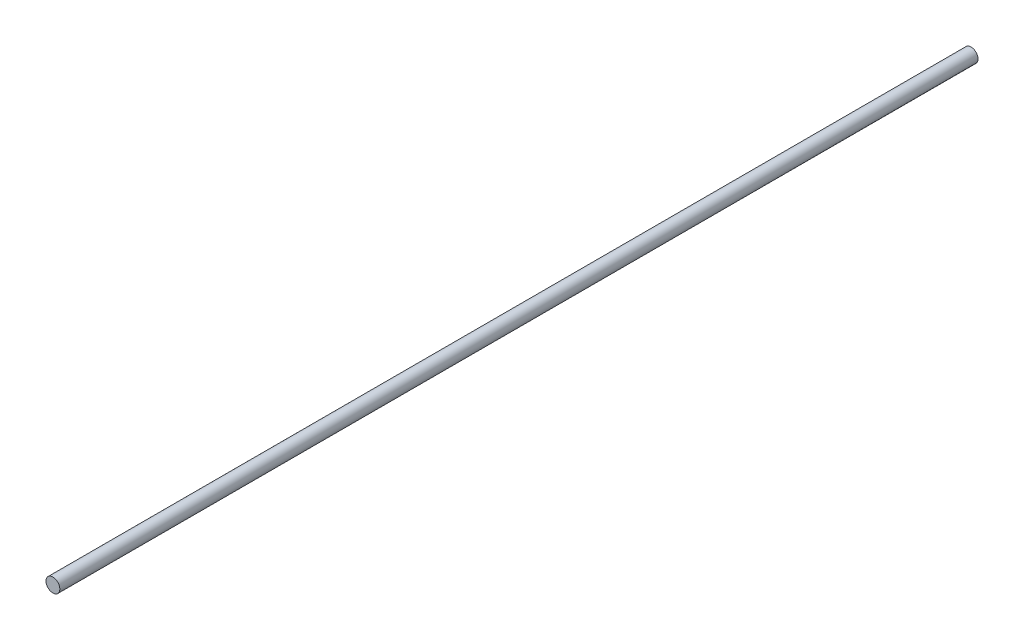
SolidWorks part; units mm, degrees
ref_plane "Front Plane" through (0, 0, 0) normal (0, 0, 1) x (1, 0, 0)
ref_plane "Top Plane" through (0, 0, 0) normal (0, 1, 0) x (1, 0, 0)
ref_plane "Right Plane" through (0, 0, 0) normal (1, 0, 0) x (0, 0, -1)
sketch "Sketch1" plane through (0, 0, 0) normal (0, 0, 1) x (1, 0, 0)
  circle A0 centre (0, 0) radius 4.7625
  dimension "D1" = 9.525
extrude "Boss-Extrude1" add sketch "Sketch1" along normal blind 631.19
equation "\"deflection\"= 0.009in'maximum deflection"
equation "\"diameter\" = 0.375in'dia"
equation "\"cross-sectionA\"= ( 3.14 * \"diameter\" ^ 2 ) / 4'cross sectional area"
equation "\"p\" = 400'force"
equation "\"E\"= 10000000'modulus of elasticity"
equation "\"L\"= ( \"deflection\" * \"cross-sectionA\" * \"E\" ) / \"p\""
